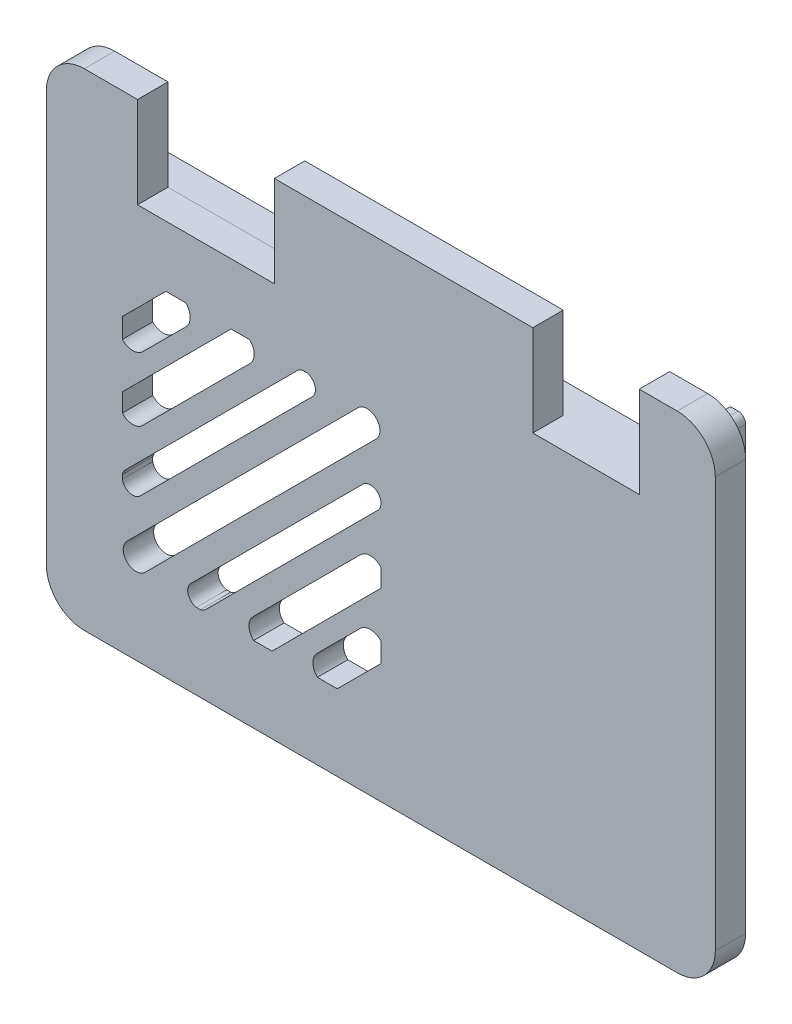
SolidWorks part; units mm, degrees
ref_plane "Front Plane" through (0, 0, 0) normal (0, 0, 1) x (1, 0, 0)
ref_plane "Top Plane" through (0, 0, 0) normal (0, 1, 0) x (1, 0, 0)
ref_plane "Right Plane" through (0, 0, 0) normal (1, 0, 0) x (0, 0, -1)
sketch "Sketch1" plane through (0, 0, 0) normal (0, 0, 1) x (1, 0, 0)
  line L0 (-16, 16) -> (-16, 10)
  line L1 (-22, -16) -> (22, -16)
  line L2 (-22, -16) -> (-22, 16)
  line L3 (-22, 16) -> (-16, 16)
  line L4 (22, -16) -> (22, 16)
  line L5 (-22, -16) -> (22, 16) construction
  line L6 (-22, 16) -> (22, -16) construction
  line L7 (-16, 10) -> (-7, 10)
  line L8 (-7, 10) -> (-7, 16)
  line L9 (10, 16) -> (10, 10)
  line L10 (10, 10) -> (17, 10)
  line L11 (17, 10) -> (17, 16)
  line L12 (-7, 16) -> (10, 16)
  line L13 (17, 16) -> (22, 16)
  point P0 (0, 0)
  dimension "D1" = 32
  dimension "D2" = 44
  dimension "D3" = 6
  dimension "D4" = 15
  dimension "D5" = 5
  dimension "D6" = 12
  dimension "D7" = 6
  dimension "D8" = 6
extrude "Boss-Extrude1" add sketch "Sketch1" along normal blind 2
fillet "Fillet1" radius 2.5 4 edges at (22, -16, 1) (-22, -16, 1) (-22, 16, 1) (22, 16, 1)
sketch3d "3DSketch1"
  line L0 (19, 14, 0) -> (19.5, 14, 0)
  line L1 (20, 13.5, 0) -> (20, -13.5, 0)
  line L2 (19.5, -14, 0) -> (-19.5, -14, 0)
  line L3 (-20, -13.5, 0) -> (-20, 13.5, 0)
  line L4 (-19.5, 14, 0) -> (-18, 14, 0)
  line L5 (-18, 14, 0) -> (-18, 8, 0)
  line L6 (-18, 8, 0) -> (-5, 8, 0)
  line L7 (-5, 8, 0) -> (-5, 14, 0)
  line L8 (-5, 14, 0) -> (8, 14, 0)
  line L9 (8, 14, 0) -> (8, 8, 0)
  line L10 (8, 8, 0) -> (19, 8, 0)
  line L11 (19, 8, 0) -> (19, 14, 0)
  line L12 (19, 14, 0) -> (19.5, 14, 0)
  line L13 (20, 13.5, 0) -> (20, -13.5, 0)
  line L14 (19.5, -14, 0) -> (-19.5, -14, 0)
  line L15 (-20, -13.5, 0) -> (-20, 13.5, 0)
  line L16 (-19.5, 14, 0) -> (-18, 14, 0)
  line L17 (-18, 14, 0) -> (-18, 9.9899, 0)
  line L19 (-5, 9.9899, 0) -> (-5, 14, 0)
  line L20 (-5, 14, 0) -> (8, 14, 0)
  line L21 (8, 14, 0) -> (8, 10, 0)
  line L23 (19, 10, 0) -> (19, 14, 0)
  line L24 (-4, 7, 0) -> (-19, 7, 0)
  line L25 (-4, 13, 0) -> (-4, 7, 0)
  line L26 (7, 13, 0) -> (-4, 13, 0)
  line L27 (7, 7, 0) -> (7, 13, 0)
  line L28 (19, 7, 0) -> (7, 7, 0)
  line L29 (19, -13, 0) -> (19, 7, 0)
  line L30 (-19, -13, 0) -> (19, -13, 0)
  line L31 (-19, 7, 0) -> (-19, -13, 0)
  line L34 (7, 13, 0) -> (-4, 13, 0)
  line L35 (7, 9, 0) -> (7, 13, 0)
  line L38 (-19, -13, 0) -> (19, -13, 0)
  line L40 (-5, 9.9899, 0) -> (-18, 9.9899, 0)
  line L41 (8, 10, 0) -> (19, 10, 0)
  line L42 (7, 9, 0) -> (19.0215, 9, 0)
  line L43 (-19, -13, 0) -> (-19, 9, 0)
  line L44 (17, 10, 0) -> (10, 10, 0) construction
  line L45 (-4, 13, 0) -> (-4, 9, 0)
  line L48 (-4, 9, 0) -> (-19, 9, 0)
  line L49 (19, -13, 0) -> (19.0215, 9, 0)
  spline S0 degree 5 poles (905.6522, 2860.992, 0) (32.7654, 1146.1923, 0) (21.3097, 290.1355, 0) (17.2775, 9.4249, 0) (18.4584, 14.0995, 0) (19.5524, 13.9979, 0) (19.564, 13.9964, 0) (19.5929, 13.9917, 0) (19.6214, 13.9853, 0) (19.6383, 13.9808, 0) (19.6717, 13.9704, 0) (19.7041, 13.957, 0) (19.7199, 13.9496, 0) (19.751, 13.9333, 0) (19.7805, 13.9144, 0) (19.7948, 13.9044, 0) (19.8226, 13.883, 0) (19.8484, 13.8593, 0) (19.8608, 13.8469, 0) (19.8844, 13.821, 0) (19.9056, 13.7931, 0) (19.9156, 13.7788, 0) (19.9344, 13.7492, 0) (19.9505, 13.718, 0) (19.9579, 13.7021, 0) (19.9711, 13.6699, 0) (19.9813, 13.6366, 0) (19.9857, 13.6198, 0) (19.9919, 13.5915, 0) (19.9965, 13.5629, 0) (19.998, 13.5514, 0) (20.0967, 12.4672, 0) (15.5127, 11.2987, 0) (295.1244, 15.2466, 0) (1147.6141, 32.782, 0) (2868.7475, -858.6471, 0) knots -6.873778 -6.873778 -6.873778 -6.873778 -6.873778 -6.873778 0.037136 0.037136 0.037136 0.111408 0.111408 0.111408 0.222815 0.222815 0.222815 0.334223 0.334223 0.334223 0.445631 0.445631 0.445631 0.557039 0.557039 0.557039 0.668446 0.668446 0.668446 0.779854 0.779854 0.779854 0.890372 0.890372 0.890372 0.963754 0.963754 0.963754 7.812942 7.812942 7.812942 7.812942 7.812942 7.812942 only from (19.5, 14, 0) to (20, 13.5, 0)
  spline S1 degree 5 poles (2867.0087, -899.6561, 0) (1152.1923, -26.7654, 0) (296.1355, -15.3097, 0) (15.4249, -11.2775, 0) (20.0995, -12.4584, 0) (19.9979, -13.5524, 0) (19.9964, -13.564, 0) (19.9917, -13.5929, 0) (19.9853, -13.6214, 0) (19.9808, -13.6383, 0) (19.9704, -13.6717, 0) (19.957, -13.7041, 0) (19.9496, -13.7199, 0) (19.9333, -13.751, 0) (19.9144, -13.7805, 0) (19.9044, -13.7948, 0) (19.883, -13.8226, 0) (19.8593, -13.8484, 0) (19.8469, -13.8608, 0) (19.821, -13.8844, 0) (19.7931, -13.9056, 0) (19.7788, -13.9156, 0) (19.7492, -13.9344, 0) (19.718, -13.9505, 0) (19.7021, -13.9579, 0) (19.6699, -13.9711, 0) (19.6366, -13.9813, 0) (19.6198, -13.9857, 0) (19.5915, -13.9919, 0) (19.5629, -13.9965, 0) (19.5514, -13.998, 0) (18.4672, -14.0967, 0) (17.2987, -9.5127, 0) (21.2466, -289.1244, 0) (38.782, -1141.6141, 0) (-852.6542, -2862.744, 0) knots -6.873778 -6.873778 -6.873778 -6.873778 -6.873778 -6.873778 0.037136 0.037136 0.037136 0.111408 0.111408 0.111408 0.222815 0.222815 0.222815 0.334223 0.334223 0.334223 0.445631 0.445631 0.445631 0.557039 0.557039 0.557039 0.668446 0.668446 0.668446 0.779854 0.779854 0.779854 0.890372 0.890372 0.890372 0.963754 0.963754 0.963754 7.812942 7.812942 7.812942 7.812942 7.812942 7.812942 only from (20, -13.5, 0) to (19.5, -14, 0)
  spline S2 degree 5 poles (-905.6404, -2861.0043, 0) (-32.7654, -1146.1923, 0) (-21.3097, -290.1355, 0) (-17.2775, -9.4249, 0) (-18.4584, -14.0995, 0) (-19.5524, -13.9979, 0) (-19.564, -13.9964, 0) (-19.5929, -13.9917, 0) (-19.6214, -13.9853, 0) (-19.6383, -13.9808, 0) (-19.6717, -13.9704, 0) (-19.7041, -13.957, 0) (-19.7199, -13.9496, 0) (-19.751, -13.9333, 0) (-19.7805, -13.9144, 0) (-19.7948, -13.9044, 0) (-19.8226, -13.883, 0) (-19.8484, -13.8593, 0) (-19.8608, -13.8469, 0) (-19.8844, -13.821, 0) (-19.9056, -13.7931, 0) (-19.9156, -13.7788, 0) (-19.9344, -13.7492, 0) (-19.9505, -13.718, 0) (-19.9579, -13.7021, 0) (-19.9711, -13.6699, 0) (-19.9813, -13.6366, 0) (-19.9857, -13.6198, 0) (-19.9919, -13.5915, 0) (-19.9965, -13.5629, 0) (-19.998, -13.5514, 0) (-20.0967, -12.4672, 0) (-15.5127, -11.2987, 0) (-295.1244, -15.2466, 0) (-1147.6141, -32.782, 0) (-2868.7497, 858.6437, 0) knots -6.873778 -6.873778 -6.873778 -6.873778 -6.873778 -6.873778 0.037136 0.037136 0.037136 0.111408 0.111408 0.111408 0.222815 0.222815 0.222815 0.334223 0.334223 0.334223 0.445631 0.445631 0.445631 0.557039 0.557039 0.557039 0.668446 0.668446 0.668446 0.779854 0.779854 0.779854 0.890372 0.890372 0.890372 0.963754 0.963754 0.963754 7.812942 7.812942 7.812942 7.812942 7.812942 7.812942 only from (-19.5, -14, 0) to (-20, -13.5, 0)
  spline S3 degree 5 poles (-2866.9977, 899.6622, 0) (-1152.1923, 26.7654, 0) (-296.1355, 15.3097, 0) (-15.4249, 11.2775, 0) (-20.0995, 12.4584, 0) (-19.9979, 13.5524, 0) (-19.9964, 13.564, 0) (-19.9917, 13.5929, 0) (-19.9853, 13.6214, 0) (-19.9808, 13.6383, 0) (-19.9704, 13.6717, 0) (-19.957, 13.7041, 0) (-19.9496, 13.7199, 0) (-19.9333, 13.751, 0) (-19.9144, 13.7805, 0) (-19.9044, 13.7948, 0) (-19.883, 13.8226, 0) (-19.8593, 13.8484, 0) (-19.8469, 13.8608, 0) (-19.821, 13.8844, 0) (-19.7931, 13.9056, 0) (-19.7788, 13.9156, 0) (-19.7492, 13.9344, 0) (-19.718, 13.9505, 0) (-19.7021, 13.9579, 0) (-19.6699, 13.9711, 0) (-19.6366, 13.9813, 0) (-19.6198, 13.9857, 0) (-19.5915, 13.9919, 0) (-19.5629, 13.9965, 0) (-19.5514, 13.998, 0) (-18.4672, 14.0967, 0) (-17.2987, 9.5127, 0) (-21.2466, 289.1244, 0) (-38.782, 1141.6141, 0) (852.6473, 2862.7428, 0) knots -6.873778 -6.873778 -6.873778 -6.873778 -6.873778 -6.873778 0.037136 0.037136 0.037136 0.111408 0.111408 0.111408 0.222815 0.222815 0.222815 0.334223 0.334223 0.334223 0.445631 0.445631 0.445631 0.557039 0.557039 0.557039 0.668446 0.668446 0.668446 0.779854 0.779854 0.779854 0.890372 0.890372 0.890372 0.963754 0.963754 0.963754 7.812942 7.812942 7.812942 7.812942 7.812942 7.812942 only from (-20, 13.5, 0) to (-19.5, 14, 0)
  spline S4 degree 5 poles (19.5, 14, 0) (19.5058, 14, 0) (19.5117, 14, 0) (19.5175, 14, 0) (19.5349, 13.9996, 0) (19.5524, 13.9979, 0) (19.564, 13.9964, 0) (19.5929, 13.9917, 0) (19.6214, 13.9853, 0) (19.6383, 13.9808, 0) (19.6717, 13.9704, 0) (19.7041, 13.957, 0) (19.7199, 13.9496, 0) (19.751, 13.9333, 0) (19.7805, 13.9144, 0) (19.7948, 13.9044, 0) (19.8226, 13.883, 0) (19.8484, 13.8593, 0) (19.8608, 13.8469, 0) (19.8844, 13.821, 0) (19.9056, 13.7931, 0) (19.9156, 13.7788, 0) (19.9344, 13.7492, 0) (19.9505, 13.718, 0) (19.9579, 13.7021, 0) (19.9711, 13.6699, 0) (19.9813, 13.6366, 0) (19.9857, 13.6198, 0) (19.9919, 13.5915, 0) (19.9965, 13.5629, 0) (19.998, 13.5514, 0) (19.9996, 13.5342, 0) (20, 13.5171, 0) (20, 13.5114, 0) (20, 13.5057, 0) (20, 13.5, 0) knots 0 0 0 0 0 0 0.037136 0.037136 0.037136 0.111408 0.111408 0.111408 0.222815 0.222815 0.222815 0.334223 0.334223 0.334223 0.445631 0.445631 0.445631 0.557039 0.557039 0.557039 0.668446 0.668446 0.668446 0.779854 0.779854 0.779854 0.890372 0.890372 0.890372 0.963754 0.963754 0.963754 1 1 1 1 1 1
  spline S5 degree 5 poles (20, -13.5, 0) (20, -13.5058, 0) (20, -13.5117, 0) (20, -13.5175, 0) (19.9996, -13.5349, 0) (19.9979, -13.5524, 0) (19.9964, -13.564, 0) (19.9917, -13.5929, 0) (19.9853, -13.6214, 0) (19.9808, -13.6383, 0) (19.9704, -13.6717, 0) (19.957, -13.7041, 0) (19.9496, -13.7199, 0) (19.9333, -13.751, 0) (19.9144, -13.7805, 0) (19.9044, -13.7948, 0) (19.883, -13.8226, 0) (19.8593, -13.8484, 0) (19.8469, -13.8608, 0) (19.821, -13.8844, 0) (19.7931, -13.9056, 0) (19.7788, -13.9156, 0) (19.7492, -13.9344, 0) (19.718, -13.9505, 0) (19.7021, -13.9579, 0) (19.6699, -13.9711, 0) (19.6366, -13.9813, 0) (19.6198, -13.9857, 0) (19.5915, -13.9919, 0) (19.5629, -13.9965, 0) (19.5514, -13.998, 0) (19.5342, -13.9996, 0) (19.5171, -14, 0) (19.5114, -14, 0) (19.5057, -14, 0) (19.5, -14, 0) knots 0 0 0 0 0 0 0.037136 0.037136 0.037136 0.111408 0.111408 0.111408 0.222815 0.222815 0.222815 0.334223 0.334223 0.334223 0.445631 0.445631 0.445631 0.557039 0.557039 0.557039 0.668446 0.668446 0.668446 0.779854 0.779854 0.779854 0.890372 0.890372 0.890372 0.963754 0.963754 0.963754 1 1 1 1 1 1
  spline S6 degree 5 poles (-19.5, -14, 0) (-19.5058, -14, 0) (-19.5117, -14, 0) (-19.5175, -14, 0) (-19.5349, -13.9996, 0) (-19.5524, -13.9979, 0) (-19.564, -13.9964, 0) (-19.5929, -13.9917, 0) (-19.6214, -13.9853, 0) (-19.6383, -13.9808, 0) (-19.6717, -13.9704, 0) (-19.7041, -13.957, 0) (-19.7199, -13.9496, 0) (-19.751, -13.9333, 0) (-19.7805, -13.9144, 0) (-19.7948, -13.9044, 0) (-19.8226, -13.883, 0) (-19.8484, -13.8593, 0) (-19.8608, -13.8469, 0) (-19.8844, -13.821, 0) (-19.9056, -13.7931, 0) (-19.9156, -13.7788, 0) (-19.9344, -13.7492, 0) (-19.9505, -13.718, 0) (-19.9579, -13.7021, 0) (-19.9711, -13.6699, 0) (-19.9813, -13.6366, 0) (-19.9857, -13.6198, 0) (-19.9919, -13.5915, 0) (-19.9965, -13.5629, 0) (-19.998, -13.5514, 0) (-19.9996, -13.5342, 0) (-20, -13.5171, 0) (-20, -13.5114, 0) (-20, -13.5057, 0) (-20, -13.5, 0) knots 0 0 0 0 0 0 0.037136 0.037136 0.037136 0.111408 0.111408 0.111408 0.222815 0.222815 0.222815 0.334223 0.334223 0.334223 0.445631 0.445631 0.445631 0.557039 0.557039 0.557039 0.668446 0.668446 0.668446 0.779854 0.779854 0.779854 0.890372 0.890372 0.890372 0.963754 0.963754 0.963754 1 1 1 1 1 1
  spline S7 degree 5 poles (-20, 13.5, 0) (-20, 13.5058, 0) (-20, 13.5117, 0) (-20, 13.5175, 0) (-19.9996, 13.5349, 0) (-19.9979, 13.5524, 0) (-19.9964, 13.564, 0) (-19.9917, 13.5929, 0) (-19.9853, 13.6214, 0) (-19.9808, 13.6383, 0) (-19.9704, 13.6717, 0) (-19.957, 13.7041, 0) (-19.9496, 13.7199, 0) (-19.9333, 13.751, 0) (-19.9144, 13.7805, 0) (-19.9044, 13.7948, 0) (-19.883, 13.8226, 0) (-19.8593, 13.8484, 0) (-19.8469, 13.8608, 0) (-19.821, 13.8844, 0) (-19.7931, 13.9056, 0) (-19.7788, 13.9156, 0) (-19.7492, 13.9344, 0) (-19.718, 13.9505, 0) (-19.7021, 13.9579, 0) (-19.6699, 13.9711, 0) (-19.6366, 13.9813, 0) (-19.6198, 13.9857, 0) (-19.5915, 13.9919, 0) (-19.5629, 13.9965, 0) (-19.5514, 13.998, 0) (-19.5342, 13.9996, 0) (-19.5171, 14, 0) (-19.5114, 14, 0) (-19.5057, 14, 0) (-19.5, 14, 0) knots 0 0 0 0 0 0 0.037136 0.037136 0.037136 0.111408 0.111408 0.111408 0.222815 0.222815 0.222815 0.334223 0.334223 0.334223 0.445631 0.445631 0.445631 0.557039 0.557039 0.557039 0.668446 0.668446 0.668446 0.779854 0.779854 0.779854 0.890372 0.890372 0.890372 0.963754 0.963754 0.963754 1 1 1 1 1 1
  dimension "D3" = 1
  dimension "D4" = 0
  dimension "D5" = 22
  dimension "D1" = 2
  dimension "D2" = 3
extrude "Boss-Extrude2" add sketch "3DSketch1" along direction (0, 0, 1) on the side of the normal blind 2
sketch "Sketch2" plane through (0, 0, 0) normal (0, 0, -1) x (-1, 0, 0)
  line L0 (-13.0108, 9) -> (-13.0108, -7.3723) construction
  line L1 (-19.0215, 9) -> (-7, 9) construction
  line L2 (-10, 16) -> (7, 16) construction
  circle A0 centre (-13.0108, 4) radius 1.5
  circle A1 centre (-13.0108, -4) radius 1.5
  dimension "D1" = 3
  dimension "D2" = 3
  dimension "D3" = 12
  dimension "D4" = 8
extrude "Boss-Extrude3" add sketch "Sketch2" along normal blind 2
sketch "Sketch3" plane through (0, 0, 0) normal (0, 0, -1) x (-1, 0, 0)
  line L0 (22, 13.5) -> (22, -13.5) construction
  line L1 (0, -11) -> (17, -11)
  line L2 (0, -11) -> (0, 6)
  line L3 (0, 6) -> (17, 6)
  line L4 (17, -11) -> (17, 6)
  line L5 (0, -11) -> (17, 6) construction
  line L6 (0, 6) -> (17, -11) construction
  line L7 (19.5, -16) -> (-19.5, -16) construction
  line L8 (16.1014, -10.1014) -> (0.8986, 5.1014) construction
  line L9 (15.5073, -10.6955) -> (0.3045, 4.5073)
  line L10 (16.6955, -9.5073) -> (1.4927, 5.6955)
  line L11 (4.9993, 5.3131) -> (16.3131, -6.0007) construction
  line L14 (16.3131, -1.758) -> (9.242, 5.3131) construction
  line L15 (15.6666, -2.4045) -> (8.5955, 4.6666)
  line L16 (16.9595, -1.1116) -> (9.8884, 5.9595)
  line L17 (16.3131, 2.4846) -> (13.4846, 5.3131) construction
  line L18 (15.6428, 1.8144) -> (12.8144, 4.6428)
  line L19 (16.9833, 3.1549) -> (14.1549, 5.9833)
  line L20 (5.4938, 5.8075) -> (16.8075, -5.5062)
  line L21 (4.5049, 4.8186) -> (15.8186, -6.4951)
  line L22 (0.6869, 1.0007) -> (12.0007, -10.3131) construction
  line L23 (0.1925, 0.5062) -> (11.5062, -10.8075)
  line L24 (1.1814, 1.4951) -> (12.4951, -9.8186)
  line L25 (7.758, -10.3131) -> (0.6869, -3.242) construction
  line L26 (8.4045, -9.6666) -> (1.3334, -2.5955)
  line L27 (7.1116, -10.9595) -> (0.0405, -3.8884)
  line L28 (3.5154, -10.3131) -> (0.6869, -7.4846) construction
  line L29 (4.1856, -9.6428) -> (1.3572, -6.8144)
  line L30 (2.8451, -10.9833) -> (0.0167, -8.1549)
  arc A0 (15.5073, -10.6955) -> (16.6955, -9.5073) centre (16.1014, -10.1014) ccw
  arc A1 (1.4927, 5.6955) -> (0.3045, 4.5073) centre (0.8986, 5.1014) ccw
  arc A4 (15.6666, -2.4045) -> (16.9595, -1.1116) centre (16.3131, -1.758) ccw
  arc A5 (9.8884, 5.9595) -> (8.5955, 4.6666) centre (9.242, 5.3131) ccw
  arc A6 (15.6428, 1.8144) -> (16.9833, 3.1549) centre (16.3131, 2.4846) ccw
  arc A7 (14.1549, 5.9833) -> (12.8144, 4.6428) centre (13.4846, 5.3131) ccw
  arc A8 (5.4938, 5.8075) -> (4.5049, 4.8186) centre (4.9993, 5.3131) ccw
  arc A9 (15.8186, -6.4951) -> (16.8075, -5.5062) centre (16.3131, -6.0007) ccw
  arc A10 (0.1925, 0.5062) -> (1.1814, 1.4951) centre (0.6869, 1.0007) cw
  arc A11 (12.4951, -9.8186) -> (11.5062, -10.8075) centre (12.0007, -10.3131) cw
  arc A12 (8.4045, -9.6666) -> (7.1116, -10.9595) centre (7.758, -10.3131) cw
  arc A13 (0.0405, -3.8884) -> (1.3334, -2.5955) centre (0.6869, -3.242) cw
  arc A14 (4.1856, -9.6428) -> (2.8451, -10.9833) centre (3.5154, -10.3131) cw
  arc A15 (0.0167, -8.1549) -> (1.3572, -6.8144) centre (0.6869, -7.4846) cw
  point P0 (8.5, -2.5)
  point P11 (8.5, -2.5)
  point P18 (10.6562, -0.3438)
  point P24 (12.7775, 1.7775)
  point P31 (14.8988, 3.8988)
  point P37 (0, 0)
  point P40 (6.3438, -4.6562)
  point P47 (4.2225, -6.7775)
  point P54 (2.1012, -8.8988)
  dimension "D1" = 5
  dimension "D2" = 5
  dimension "D3" = 17
  dimension "D4" = 17
  dimension "D5" = 21.5
  dimension "D6" = 16
  dimension "D7" = 10
  dimension "D8" = 4
  dimension "D9" = 3.0493
  dimension "D10" = 3
  dimension "D11" = 3
extrude "Cut-Extrude2" cut sketch "Sketch3" against normal through all contours A15 L30 A14 L1 L29 L2 | A13 L27 A12 L1 L26 L2 | A11 L1 L24 A10 L2 L23 | L10 A1 L9 A0 | L4 A9 L20 A8 L3 L21 | L16 A5 L3 L15 A4 L4 | L19 A7 L3 L18 A6 L4
